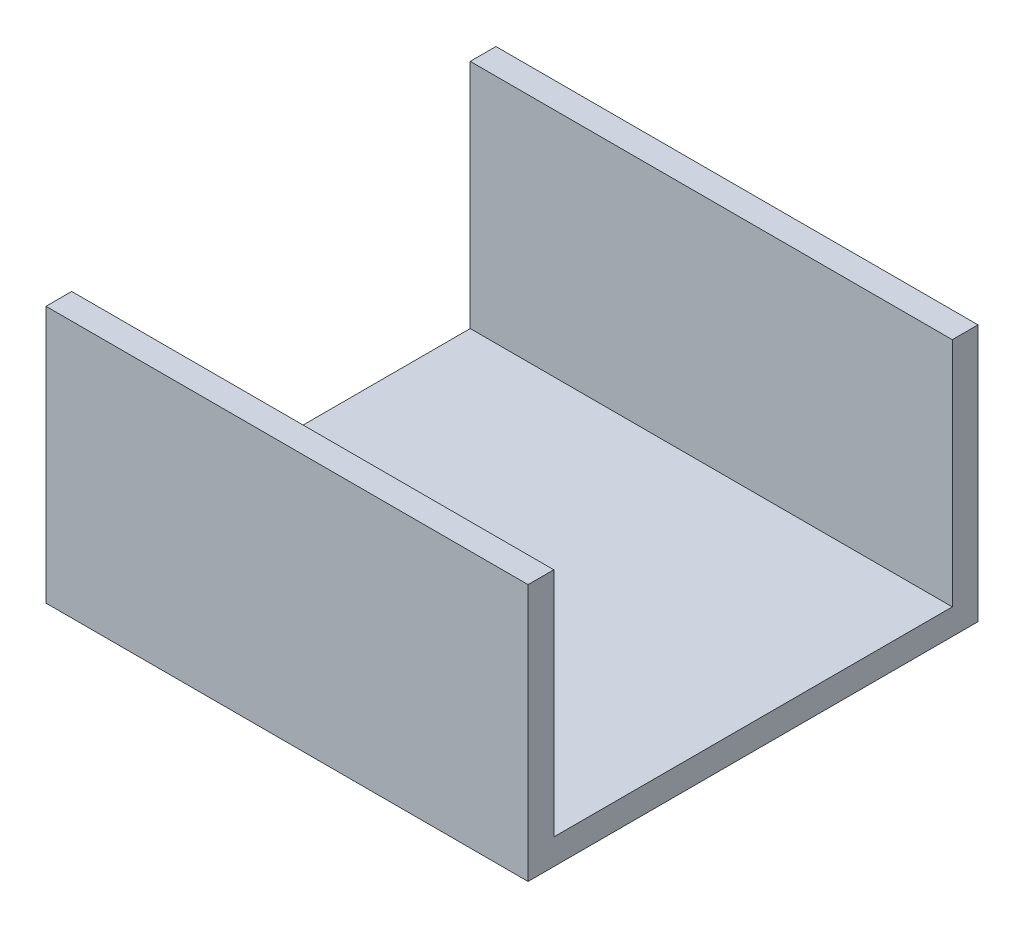
SolidWorks part; units mm, degrees
ref_plane "정면" through (0, 0, 0) normal (0, 0, 1) x (1, 0, 0)
ref_plane "윗면" through (0, 0, 0) normal (0, 1, 0) x (1, 0, 0)
ref_plane "우측면" through (0, 0, 0) normal (1, 0, 0) x (0, 0, -1)
sketch "스케치1" plane through (0, 0, 0) normal (0, 1, 0) x (1, 0, 0)
  line L1 (0, 0) -> (75, 0)
  line L2 (0, 0) -> (0, 70)
  line L3 (0, 70) -> (75, 70)
  line L4 (75, 0) -> (75, 70)
  dimension "D1" = 70
  dimension "D2" = 75
extrude "보스-돌출1" add sketch "스케치1" along normal blind 4
sketch "스케치2" plane through (0, 4, 0) normal (0, 1, 0) x (1, 0, 0)
  line L0 (75, 0) -> (75, 70) construction
  line L1 (0, 0) -> (75, 0)
  line L2 (0, 0) -> (0, 4)
  line L3 (0, 4) -> (75, 4)
  line L4 (75, 0) -> (75, 4)
  line L5 (0, 70) -> (0, 0) construction
  line L6 (75, 70) -> (0, 70)
  line L7 (75, 70) -> (75, 66)
  line L8 (75, 66) -> (0, 66)
  line L9 (0, 70) -> (0, 66)
  dimension "D1" = 4
  dimension "D2" = 4
extrude "보스-돌출2" add sketch "스케치2" along normal blind 36
